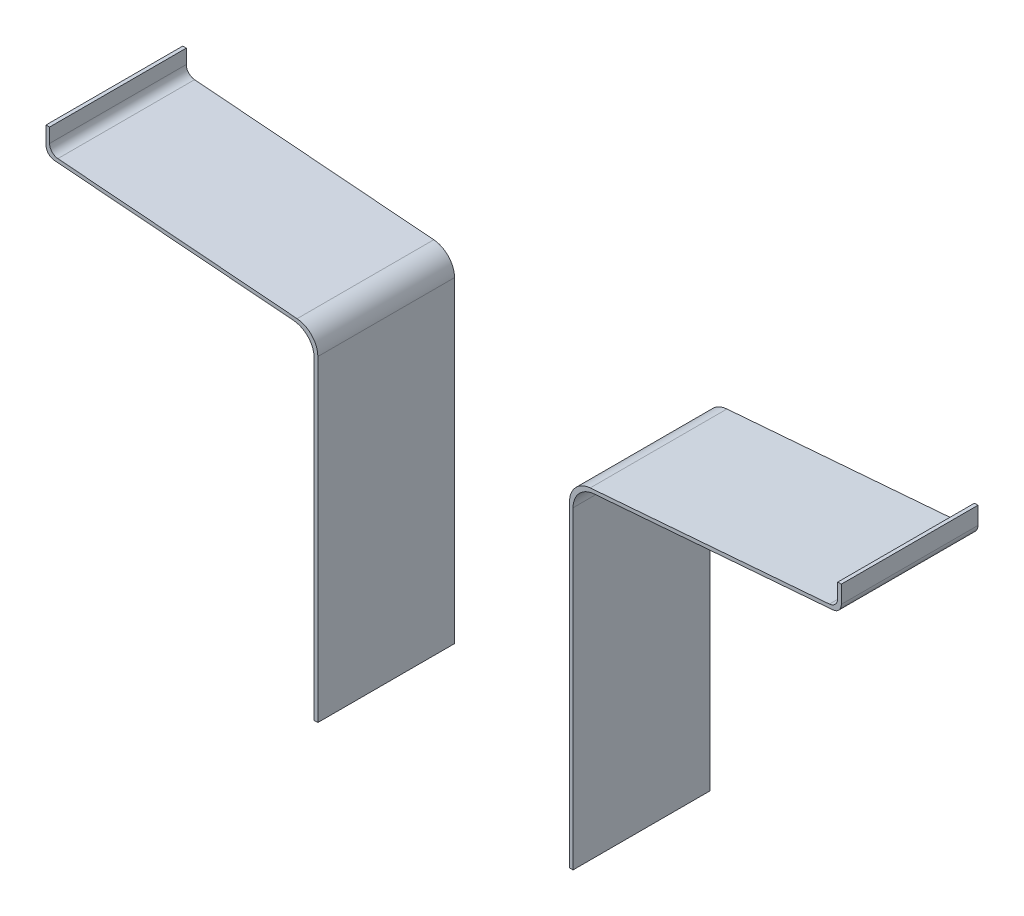
SolidWorks part; units mm, degrees
ref_plane "Front Plane" through (0, 0, 0) normal (0, 0, 1) x (1, 0, 0)
ref_plane "Top Plane" through (0, 0, 0) normal (0, 1, 0) x (1, 0, 0)
ref_plane "Right Plane" through (0, 0, 0) normal (1, 0, 0) x (0, 0, -1)
sketch "Sketch1" plane through (0, 0, 0) normal (0, 0, 1) x (1, 0, 0)
  line L0 (0, 0) -> (350, 0) construction
  line L1 (350, -10) -> (230.88, -19.4688)
  line L2 (350, 0) -> (351.5875, 0)
  line L3 (350, 0) -> (350, -10)
  line L5 (351.5875, 0) -> (351.5875, -11.4688)
  line L6 (230.88, -19.4688) -> (230.88, -169.4688)
  line L7 (230.88, -169.4688) -> (232.47, -169.4688)
  line L8 (232.47, -169.4688) -> (232.47, -20.9375)
  line L9 (232.47, -20.9375) -> (351.5875, -11.4688)
  line L10 (175, 0) -> (175, 33.051) construction
  line L11 (0, 0) -> (-1.5875, 0)
  line L12 (-1.5875, 0) -> (-1.5875, -11.4688)
  line L13 (0, 0) -> (0, -10)
  line L14 (117.53, -20.9375) -> (-1.5875, -11.4688)
  line L15 (0, -10) -> (119.12, -19.4688)
  line L16 (117.53, -169.4688) -> (117.53, -20.9375)
  line L17 (119.12, -169.4688) -> (117.53, -169.4688)
  line L18 (119.12, -19.4688) -> (119.12, -169.4688)
  point P19 (119.12, -23.6754)
  dimension "D1" = 350
  dimension "D2" = 10
  dimension "D3" = 1.5875
  dimension "D4" = 150
  dimension "D5" = 1.59
  dimension "D6" = 1.59
  dimension "D7" = 55.88
  dimension "D8" = 8
extrude "Boss-Extrude1" add sketch "Sketch1" along normal blind 60.7
fillet "Fillet1" radius 10 2 edges at (230.88, -19.4688, 30.35) (232.47, -20.9375, 30.35)
fillet "Fillet2" radius 10 2 edges at (119.12, -19.4688, 30.35) (117.53, -20.9375, 30.35)
fillet "Fillet3" radius 4 2 edges at (350, -10, 30.35) (351.5875, -11.4688, 30.35)
fillet "Fillet4" radius 4 2 edges at (-1.5875, -11.4688, 30.35) (0, -10, 30.35)
